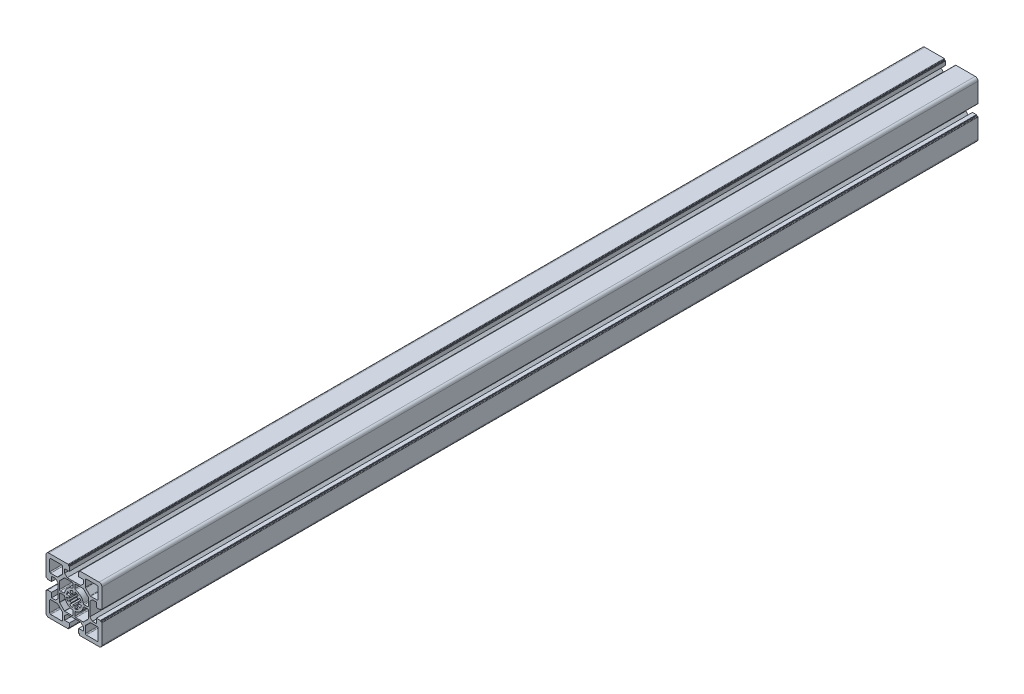
SolidWorks part; units mm, degrees
ref_plane "Front Plane" through (0, 0, 0) normal (0, 0, 1) x (1, 0, 0)
ref_plane "Top Plane" through (0, 0, 0) normal (0, 1, 0) x (1, 0, 0)
ref_plane "Right Plane" through (0, 0, 0) normal (1, 0, 0) x (0, 0, -1)
sketch "Sketch1" plane through (0, 0, 0) normal (0, 0, 1) x (1, 0, 0)
  line L0 (25, 12.3) -> (17.9642, 12.3)
  line L1 (17.2571, 12.5929) -> (12.5929, 17.2571)
  line L2 (12.3, 17.9642) -> (12.3, 25)
  line L3 (25, 26) -> (13.3, 26)
  line L4 (26, 13.3) -> (26, 25)
  line L5 (-0.8683, 4.924) -> (-1.3892, 7.8785)
  line L6 (-4.5886, 6.5532) -> (-2.8679, 4.0958)
  line L7 (-4.0958, 2.8679) -> (-6.5532, 4.5886)
  line L8 (-7.8785, 1.3892) -> (-4.9241, 0.8683)
  line L9 (14.5, 1) -> (10.9691, 1)
  line L10 (15.5, 2) -> (15.5, 9.9003)
  line L11 (15.3535, 10.2538) -> (10.2538, 15.3536)
  line L12 (9.9002, 15.5) -> (2, 15.5)
  line L13 (1, 10.9692) -> (1, 14.5)
  line L14 (7.25, 17) -> (0, 17)
  line L15 (10.05, 19.8) -> (7.25, 17)
  line L16 (10.05, 24) -> (10.05, 19.8)
  line L17 (5, 24) -> (10.05, 24)
  line L18 (5, 28.2) -> (5, 24)
  line L19 (5.5, 28.5) -> (5.3, 28.5)
  line L20 (5.8, 28.8) -> (5.8, 29.5)
  line L21 (27, 30) -> (6.3, 30)
  line L22 (30, 6.3) -> (30, 27)
  line L23 (29.5, 5.8) -> (28.8, 5.8)
  line L24 (28.5, 5.3) -> (28.5, 5.5)
  line L25 (24, 5) -> (28.2, 5)
  line L26 (24, 10.05) -> (24, 5)
  line L27 (19.8, 10.05) -> (24, 10.05)
  line L28 (17, 7.25) -> (19.8, 10.05)
  line L29 (17, 7.25) -> (17, 0)
  line L30 (7.8784, 1.3892) -> (4.924, 0.8683)
  line L31 (4.0957, 2.8679) -> (6.5532, 4.5886)
  line L32 (4.5886, 6.5532) -> (2.8679, 4.0958)
  line L33 (0.8682, 4.924) -> (1.3892, 7.8785)
  line L34 (-25, -12.3) -> (-17.9642, -12.3)
  line L35 (-17.2571, -12.5929) -> (-12.5929, -17.2571)
  line L36 (-12.3, -17.9642) -> (-12.3, -25)
  line L37 (-25, -26) -> (-13.3, -26)
  line L38 (-26, -13.3) -> (-26, -25)
  line L39 (-14.5, -1) -> (-10.9692, -1)
  line L40 (-15.5, -2) -> (-15.5, -9.9002)
  line L41 (-17, 7.25) -> (-17, 0)
  line L42 (-17, 7.25) -> (-19.8, 10.05)
  line L43 (-19.8, 10.05) -> (-24, 10.05)
  line L44 (-24, 10.05) -> (-24, 5)
  line L45 (-24, 5) -> (-28.2, 5)
  line L46 (-28.5, 5.3) -> (-28.5, 5.5)
  line L47 (-29.5, 5.8) -> (-28.8, 5.8)
  line L48 (-30, 6.3) -> (-30, 27)
  line L49 (-27, 30) -> (-6.3, 30)
  line L50 (-5.8, 28.8) -> (-5.8, 29.5)
  line L51 (-5.5, 28.5) -> (-5.3, 28.5)
  line L52 (-5, 28.2) -> (-5, 24)
  line L53 (-5, 24) -> (-10.05, 24)
  line L54 (-10.05, 24) -> (-10.05, 19.8)
  line L55 (-10.05, 19.8) -> (-7.25, 17)
  line L56 (-7.25, 17) -> (0, 17)
  line L57 (-15.3536, -10.2538) -> (-10.2538, -15.3535)
  line L58 (-9.9003, -15.5) -> (-2, -15.5)
  line L59 (-1, -10.9691) -> (-1, -14.5)
  line L60 (-7.25, -17) -> (0, -17)
  line L61 (-10.05, -19.8) -> (-7.25, -17)
  line L62 (-10.05, -24) -> (-10.05, -19.8)
  line L63 (-5, -24) -> (-10.05, -24)
  line L64 (-5, -28.2) -> (-5, -24)
  line L65 (-5.5, -28.5) -> (-5.3, -28.5)
  line L66 (-5.8, -28.8) -> (-5.8, -29.5)
  line L67 (-27, -30) -> (-6.3, -30)
  line L68 (-30, -6.3) -> (-30, -27)
  line L69 (-29.5, -5.8) -> (-28.8, -5.8)
  line L70 (-28.5, -5.3) -> (-28.5, -5.5)
  line L71 (-24, -5) -> (-28.2, -5)
  line L72 (-24, -10.05) -> (-24, -5)
  line L73 (-19.8, -10.05) -> (-24, -10.05)
  line L74 (-17, -7.25) -> (-19.8, -10.05)
  line L75 (-17, 0) -> (-17, -7.25)
  line L76 (0.8682, -4.924) -> (1.3892, -7.8784)
  line L77 (4.5886, -6.5532) -> (2.8679, -4.0957)
  line L78 (4.0957, -2.8679) -> (6.5532, -4.5886)
  line L79 (7.8784, -1.3892) -> (4.924, -0.8682)
  line L80 (17, 0) -> (17, -7.25)
  line L81 (17, -7.25) -> (19.8, -10.05)
  line L82 (19.8, -10.05) -> (24, -10.05)
  line L83 (24, -10.05) -> (24, -5)
  line L84 (24, -5) -> (28.2, -5)
  line L85 (28.5, -5.3) -> (28.5, -5.5)
  line L86 (29.5, -5.8) -> (28.8, -5.8)
  line L87 (30, -6.3) -> (30, -27)
  line L88 (27, -30) -> (6.3, -30)
  line L89 (5.8, -28.8) -> (5.8, -29.5)
  line L90 (5.5, -28.5) -> (5.3, -28.5)
  line L91 (5, -28.2) -> (5, -24)
  line L92 (5, -24) -> (10.05, -24)
  line L93 (10.05, -24) -> (10.05, -19.8)
  line L94 (10.05, -19.8) -> (7.25, -17)
  line L95 (7.25, -17) -> (0, -17)
  line L96 (1, -10.9691) -> (1, -14.5)
  line L97 (9.9002, -15.5) -> (2, -15.5)
  line L98 (15.3535, -10.2538) -> (10.2538, -15.3535)
  line L99 (15.5, -2) -> (15.5, -9.9002)
  line L100 (-1, 10.9692) -> (-1, 14.5)
  line L101 (-9.9003, 15.5) -> (-2, 15.5)
  line L102 (-15.3536, 10.2538) -> (-10.2538, 15.3536)
  line L103 (-15.5, 2) -> (-15.5, 9.9003)
  line L104 (-14.5, 1) -> (-10.9692, 1)
  line L105 (-26, 13.3) -> (-26, 25)
  line L106 (-25, 26) -> (-13.3, 26)
  line L107 (-12.3, 17.9642) -> (-12.3, 25)
  line L108 (-17.2571, 12.5929) -> (-12.5929, 17.2571)
  line L109 (-25, 12.3) -> (-17.9642, 12.3)
  line L110 (14.5, -1) -> (10.9691, -1)
  line L111 (-7.8785, -1.3892) -> (-4.9241, -0.8682)
  line L112 (-4.0958, -2.8679) -> (-6.5532, -4.5886)
  line L113 (-4.5886, -6.5532) -> (-2.8679, -4.0957)
  line L114 (-0.8683, -4.924) -> (-1.3892, -7.8784)
  line L115 (26, -13.3) -> (26, -25)
  line L116 (25, -26) -> (13.3, -26)
  line L117 (12.3, -17.9642) -> (12.3, -25)
  line L118 (17.2571, -12.5929) -> (12.5929, -17.2571)
  line L119 (25, -12.3) -> (17.9642, -12.3)
  line L120 (0, 0) -> (0, 50.387) construction
  line L121 (0, 0) -> (0, -41.9308) construction
  line L122 (0, 0) -> (51.9943, 0) construction
  line L123 (0, 0) -> (-54.8745, 0) construction
  arc A0 (17.9642, 12.3) -> (17.2571, 12.5929) centre (17.9642, 13.3) cw
  arc A1 (12.5929, 17.2571) -> (12.3, 17.9642) centre (13.3, 17.9642) cw
  arc A2 (12.3, 25) -> (13.3, 26) centre (13.3, 25) cw
  arc A3 (25, 26) -> (26, 25) centre (25, 25) cw
  arc A4 (26, 13.3) -> (25, 12.3) centre (25, 13.3) cw
  arc A5 (0, 5) -> (-0.8683, 4.924) centre (0, 0) ccw
  arc A6 (-1.3892, 7.8785) -> (-4.5886, 6.5532) centre (0, 0) ccw
  arc A7 (-2.8679, 4.0958) -> (-4.0958, 2.8679) centre (0, 0) ccw
  arc A8 (-6.5532, 4.5886) -> (-7.8785, 1.3892) centre (0, 0) ccw
  arc A9 (-4.9241, 0.8683) -> (-4.9241, -0.8682) centre (0, 0) ccw
  arc A10 (15.5, 2) -> (14.5, 1) centre (14.5, 2) cw
  arc A11 (15.3535, 10.2538) -> (15.5, 9.9003) centre (15, 9.9003) cw
  arc A12 (9.9002, 15.5) -> (10.2538, 15.3536) centre (9.9002, 15) cw
  arc A13 (1, 14.5) -> (2, 15.5) centre (2, 14.5) cw
  arc A14 (1.8206, 9.9854) -> (1, 10.9692) centre (2, 10.9692) cw
  arc A15 (1.8206, 9.9854) -> (9.9853, 1.8206) centre (0, 0) cw
  arc A16 (10.9691, 1) -> (9.9853, 1.8206) centre (10.9691, 2) cw
  arc A17 (5, 28.2) -> (5.3, 28.5) centre (5.3, 28.2) cw
  arc A18 (5.8, 28.8) -> (5.5, 28.5) centre (5.5, 28.8) cw
  arc A19 (5.8, 29.5) -> (6.3, 30) centre (6.3, 29.5) cw
  arc A20 (27, 30) -> (30, 27) centre (27, 27) cw
  arc A21 (30, 6.3) -> (29.5, 5.8) centre (29.5, 6.3) cw
  arc A22 (28.5, 5.5) -> (28.8, 5.8) centre (28.8, 5.5) cw
  arc A23 (28.5, 5.3) -> (28.2, 5) centre (28.2, 5.3) cw
  arc A24 (4.924, 0.8683) -> (4.924, -0.8682) centre (0, 0) cw
  arc A25 (6.5532, 4.5886) -> (7.8784, 1.3892) centre (0, 0) cw
  arc A26 (2.8679, 4.0958) -> (4.0957, 2.8679) centre (0, 0) cw
  arc A27 (1.3892, 7.8785) -> (4.5886, 6.5532) centre (0, 0) cw
  arc A28 (-28.5, 5.3) -> (-28.2, 5) centre (-28.2, 5.3) ccw
  arc A29 (-28.5, 5.5) -> (-28.8, 5.8) centre (-28.8, 5.5) ccw
  arc A30 (-30, 6.3) -> (-29.5, 5.8) centre (-29.5, 6.3) ccw
  arc A31 (-27, 30) -> (-30, 27) centre (-27, 27) ccw
  arc A32 (-5.8, 29.5) -> (-6.3, 30) centre (-6.3, 29.5) ccw
  arc A33 (-5.8, 28.8) -> (-5.5, 28.5) centre (-5.5, 28.8) ccw
  arc A34 (-5, 28.2) -> (-5.3, 28.5) centre (-5.3, 28.2) ccw
  arc A35 (0, 5) -> (0.8682, 4.924) centre (0, 0) cw
  arc A36 (-17.9642, -12.3) -> (-17.2571, -12.5929) centre (-17.9642, -13.3) cw
  arc A37 (-12.5929, -17.2571) -> (-12.3, -17.9642) centre (-13.3, -17.9642) cw
  arc A38 (-12.3, -25) -> (-13.3, -26) centre (-13.3, -25) cw
  arc A39 (-25, -26) -> (-26, -25) centre (-25, -25) cw
  arc A40 (-26, -13.3) -> (-25, -12.3) centre (-25, -13.3) cw
  arc A41 (-15.5, -2) -> (-14.5, -1) centre (-14.5, -2) cw
  arc A42 (-15.3536, -10.2538) -> (-15.5, -9.9002) centre (-15, -9.9002) cw
  arc A43 (-9.9003, -15.5) -> (-10.2538, -15.3535) centre (-9.9003, -15) cw
  arc A44 (-1, -14.5) -> (-2, -15.5) centre (-2, -14.5) cw
  arc A45 (-1.8206, -9.9853) -> (-1, -10.9691) centre (-2, -10.9691) cw
  arc A46 (-1.8206, -9.9853) -> (-9.9854, -1.8206) centre (0, 0) cw
  arc A47 (-10.9692, -1) -> (-9.9854, -1.8206) centre (-10.9692, -2) cw
  arc A48 (0, -4.9999) -> (0.8682, -4.924) centre (0, 0) ccw
  arc A49 (-5, -28.2) -> (-5.3, -28.5) centre (-5.3, -28.2) cw
  arc A50 (-5.8, -28.8) -> (-5.5, -28.5) centre (-5.5, -28.8) cw
  arc A51 (-5.8, -29.5) -> (-6.3, -30) centre (-6.3, -29.5) cw
  arc A52 (-27, -30) -> (-30, -27) centre (-27, -27) cw
  arc A53 (-30, -6.3) -> (-29.5, -5.8) centre (-29.5, -6.3) cw
  arc A54 (-28.5, -5.5) -> (-28.8, -5.8) centre (-28.8, -5.5) cw
  arc A55 (-28.5, -5.3) -> (-28.2, -5) centre (-28.2, -5.3) cw
  arc A56 (1.3892, -7.8784) -> (4.5886, -6.5532) centre (0, 0) ccw
  arc A57 (2.8679, -4.0957) -> (4.0957, -2.8679) centre (0, 0) ccw
  arc A58 (6.5532, -4.5886) -> (7.8784, -1.3892) centre (0, 0) ccw
  arc A59 (28.5, -5.3) -> (28.2, -5) centre (28.2, -5.3) ccw
  arc A60 (28.5, -5.5) -> (28.8, -5.8) centre (28.8, -5.5) ccw
  arc A61 (30, -6.3) -> (29.5, -5.8) centre (29.5, -6.3) ccw
  arc A62 (27, -30) -> (30, -27) centre (27, -27) ccw
  arc A63 (5.8, -29.5) -> (6.3, -30) centre (6.3, -29.5) ccw
  arc A64 (5.8, -28.8) -> (5.5, -28.5) centre (5.5, -28.8) ccw
  arc A65 (5, -28.2) -> (5.3, -28.5) centre (5.3, -28.2) ccw
  arc A66 (10.9691, -1) -> (9.9853, -1.8206) centre (10.9691, -2) ccw
  arc A67 (1.8206, -9.9853) -> (9.9853, -1.8206) centre (0, 0) ccw
  arc A68 (-10.9692, 1) -> (-9.9854, 1.8206) centre (-10.9692, 2) ccw
  arc A69 (-1.8206, 9.9854) -> (-9.9854, 1.8206) centre (0, 0) ccw
  arc A70 (-1.8206, 9.9854) -> (-1, 10.9692) centre (-2, 10.9692) ccw
  arc A71 (-1, 14.5) -> (-2, 15.5) centre (-2, 14.5) ccw
  arc A72 (-9.9003, 15.5) -> (-10.2538, 15.3536) centre (-9.9003, 15) ccw
  arc A73 (-15.3536, 10.2538) -> (-15.5, 9.9003) centre (-15, 9.9003) ccw
  arc A74 (-15.5, 2) -> (-14.5, 1) centre (-14.5, 2) ccw
  arc A75 (-26, 13.3) -> (-25, 12.3) centre (-25, 13.3) ccw
  arc A76 (-25, 26) -> (-26, 25) centre (-25, 25) ccw
  arc A77 (-12.3, 25) -> (-13.3, 26) centre (-13.3, 25) ccw
  arc A78 (-12.5929, 17.2571) -> (-12.3, 17.9642) centre (-13.3, 17.9642) ccw
  arc A79 (-17.9642, 12.3) -> (-17.2571, 12.5929) centre (-17.9642, 13.3) ccw
  arc A80 (1.8206, -9.9853) -> (1, -10.9691) centre (2, -10.9691) ccw
  arc A81 (1, -14.5) -> (2, -15.5) centre (2, -14.5) ccw
  arc A82 (9.9002, -15.5) -> (10.2538, -15.3535) centre (9.9002, -15) ccw
  arc A83 (15.3535, -10.2538) -> (15.5, -9.9002) centre (15, -9.9002) ccw
  arc A84 (15.5, -2) -> (14.5, -1) centre (14.5, -2) ccw
  arc A85 (-6.5532, -4.5886) -> (-7.8785, -1.3892) centre (0, 0) cw
  arc A86 (-2.8679, -4.0957) -> (-4.0958, -2.8679) centre (0, 0) cw
  arc A87 (-1.3892, -7.8784) -> (-4.5886, -6.5532) centre (0, 0) cw
  arc A88 (0, -4.9999) -> (-0.8683, -4.924) centre (0, 0) cw
  arc A89 (26, -13.3) -> (25, -12.3) centre (25, -13.3) ccw
  arc A90 (25, -26) -> (26, -25) centre (25, -25) ccw
  arc A91 (12.3, -25) -> (13.3, -26) centre (13.3, -25) ccw
  arc A92 (12.5929, -17.2571) -> (12.3, -17.9642) centre (13.3, -17.9642) ccw
  arc A93 (17.9642, -12.3) -> (17.2571, -12.5929) centre (17.9642, -13.3) ccw
  dimension "D6" = 13
  dimension "D4" = 10
  dimension "D1" = 60
  dimension "D2" = 60
  dimension "D3" = 30
  dimension "D5" = 10
extrude "Base-Extrude" add sketch "Sketch1" against normal blind 940
scale "Escala1" scale about origin uniform scaling yes scale factor 0.5
